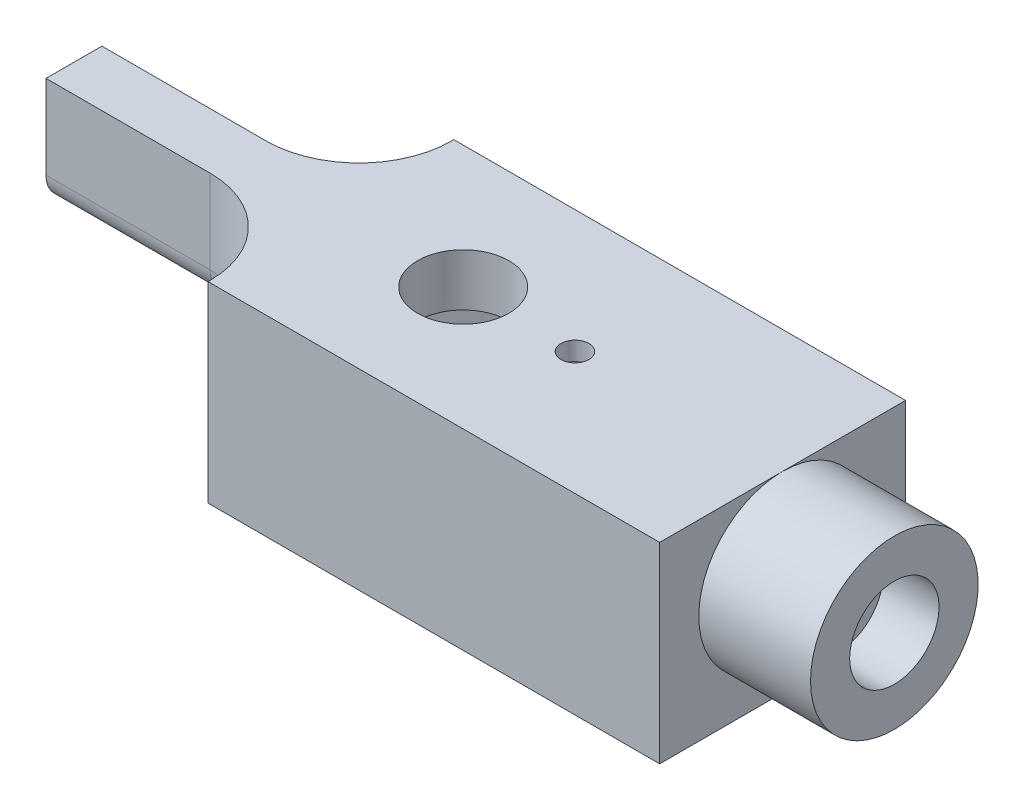
SolidWorks part; units mm, degrees
ref_plane "Plan de face" through (0, 0, 0) normal (0, 0, 1) x (1, 0, 0)
ref_plane "Plan de dessus" through (0, 0, 0) normal (0, 1, 0) x (1, 0, 0)
ref_plane "Plan de droite" through (0, 0, 0) normal (1, 0, 0) x (0, 0, -1)
sketch "Esquisse1" plane through (0, 0, 0) normal (0, 1, 0) x (1, 0, 0)
  line L0 (0, 5.5) -> (22.05, 5.5) construction
  line L1 (0, 0) -> (22.05, 0) construction
  line L2 (0, 0) -> (0, 11) construction
  line L3 (0, 11) -> (22.05, 11) construction
  line L4 (22.05, 0) -> (22.05, 11) construction
  line L5 (22.05, 11) -> (13.95, 0) construction
  line L6 (13.95, 0) -> (13.95, 11) construction
  line L7 (16.45, 11) -> (13.95, 8.5) construction
  line L8 (16.45, 0) -> (16.45, 11) construction
  line L10 (13.95, 2.5) -> (16.45, 0) construction
  circle A0 centre (6, 5.5) radius 5 construction
  circle A1 centre (12, 5.5) radius 5 construction
  circle A2 centre (18, 5.5) radius 1.25 construction
  point P14 (1, 5.5)
  dimension "D1" = 10
  dimension "D3" = 2.5
  dimension "D2" = 6
  dimension "D4" = 6
  dimension "D5" = 1
  dimension "D6" = 11
  dimension "D7" = 8.1
  dimension "D8" = 2.5
sketch "Esquisse2" plane through (0, 0, 0) normal (0, 1, 0) x (1, 0, 0)
  line L0 (11.025, 11) -> (11.025, 12.1) construction
  line L1 (0, 11) -> (22.05, 11)
  line L2 (0, 11) -> (0, 0)
  line L3 (0, 0) -> (22.05, 0)
  line L4 (22.05, 11) -> (22.05, 0)
  line L5 (-1.1, 12.1) -> (23.15, 12.1)
  line L6 (-1.1, 12.1) -> (-1.1, -1.1)
  line L7 (-1.1, -1.1) -> (23.15, -1.1)
  line L8 (23.15, 12.1) -> (23.15, -1.1)
  line L9 (0, 2.5) -> (2.5, 0)
  line L10 (-1.1, 5.5) -> (0, 5.5) construction
  line L12 (22.05, 8.5) -> (19.55, 11)
  line L13 (19.55, 11) -> (19.55, 0) construction
  line L14 (19.55, 0) -> (22.05, 2.5)
  line L15 (0.5, 0.5) -> (21.55, 0.5) construction
  line L16 (2.5, 11) -> (0, 8.5)
  line L18 (0.5, 0.5) -> (0.5, 10.5) construction
  line L19 (0.5, 10.5) -> (21.55, 10.5) construction
  line L20 (21.55, 0.5) -> (21.55, 10.5) construction
  circle A0 centre (0.5, 0.5) radius 0.5
  circle A1 centre (21.55, 0.5) radius 0.5
  circle A2 centre (21.55, 10.5) radius 0.5
  circle A3 centre (0.5, 10.5) radius 0.5
  dimension "D3" = 1
  dimension "D1" = 1.1
  dimension "D2" = 2.5
extrude "Boss.-Extru.1" add sketch "Esquisse2" along normal blind 9.3 contours L8 L5 L6 L7 L1 L4 L3 L2 | L16 L1 L2 | L12 L4 L1 | L14 L3 L4 | A1 L3 L4 | A2 L4 L1 | A0 L2 L3 | A3 L1 L2 | A0 L3 L9 L2
sketch "Esquisse3" plane through (0, 9.3, 0) normal (0, 1, 0) x (1, 0, 0)
  line L0 (-1.1, 12.1) -> (-1.1, -1.1) construction
  line L1 (23.15, -1.1) -> (-1.1, -1.1)
  line L2 (23.15, -1.1) -> (23.15, 12.1)
  line L3 (23.15, 12.1) -> (-1.1, 12.1)
  line L4 (-1.1, -1.1) -> (-1.1, 12.1)
  line L5 (-1.1, 12.1) -> (23.15, 12.1) construction
  circle A0 centre (6, 5.5) radius 2.45
  circle A1 centre (12, 5.5) radius 0.75
  dimension "D1" = 4.9
  dimension "D2" = 1.5
extrude "Boss.-Extru.2" add sketch "Esquisse3" along normal blind 1
sketch "Esquisse4" plane through (23.15, 0, 0) normal (1, 0, 0) x (0, 0, -1)
  line L0 (-1.1, 9.3) -> (12.1, 9.3) construction
  line L1 (-1.1, 10.3) -> (-1.1, 0) construction
  line L2 (12.1, 10.3) -> (12.1, 0) construction
  line L3 (-1.1, 10.3) -> (12.1, 10.3) construction
  line L4 (5.5, 5.8) -> (5.5, 9.3) construction
  circle A0 centre (5.5, 5.8) radius 3.5 construction
  circle A1 centre (5.5, 5.8) radius 1
  dimension "D1" = 1
  dimension "D2" = 7
  dimension "D3" = 2
extrude "Enlèv. mat.-Extru.1" cut sketch "Esquisse4" against normal through all
ref_axis "Axe1" through (-19.0316, 5.8, -5.5) along (1, 0, 0)
ref_plane "Plan1" through (0, 0, -5.5) normal (0, 0, 1) x (1, 0, 0)
sketch "Esquisse5" plane through (0, 0, -5.5) normal (0, 0, 1) x (1, 0, 0)
  line L1 (26.15, 5.8) -> (26.15, 8.2)
  line L2 (26.15, 8.2) -> (29.15, 8.2)
  line L3 (29.15, 8.2) -> (29.15, 10.3)
  line L4 (29.15, 10.3) -> (22.05, 10.3)
  line L5 (22.05, 10.3) -> (22.05, 5.8)
  line L8 (-19.0316, 5.8) -> (28.6752, 5.8) construction
  line L9 (23.15, 10.3) -> (-1.1, 10.3) construction
  line L10 (26.15, 8.2) -> (22.05, 8.2) construction
  line L11 (22.05, 5.8) -> (26.15, 5.8)
  line L12 (0.9, 5.8) -> (0.9, 6.3)
  line L13 (0.9, 6.3) -> (-1.1, 6.3)
  line L14 (-1.1, 6.3) -> (-1.1, 7.3) construction
  line L15 (-1.1, 7.3) -> (1.9, 7.3)
  line L16 (1.9, 7.3) -> (1.9, 5.8)
  line L17 (1.9, 5.8) -> (0.9, 5.8)
  line L19 (23.15, 10.3) -> (23.15, 0) construction
  line L21 (22.05, 9.3) -> (22.05, 0) construction
  line L22 (-1.1, 5.8) -> (-1.1, 0) construction
  line L24 (-1.1, 7.3) -> (-14.9, 7.3)
  line L25 (-1.1, 7.3) -> (-1.1, 6.3)
  line L26 (-1.1, 6.3) -> (-14.9, 6.3)
  line L27 (-14.9, 7.3) -> (-14.9, 6.3)
  dimension "D1" = 3
  dimension "D2" = 2.4
  dimension "D3" = 1
  dimension "D4" = 0.5
  dimension "D5" = 1
  dimension "D6" = 3
  dimension "D7" = 13.8
  dimension "D8" = 3
revolve "Révolution1" add sketch "Esquisse5" angle 360 about axis through (-19.0316, 5.8, -5.5) along (1, 0, 0)
sketch "Esquisse6" plane through (-14.9, 0, 0) normal (-1, 0, 0) x (0, 0, 1)
  line L0 (-12.1, 10.3) -> (1.1, 10.3) construction
  line L1 (-7, 5.8) -> (-4, 5.8) construction
  line L2 (-7, 5.8) -> (-7, 10.3)
  line L3 (-7, 10.3) -> (-4, 10.3)
  line L4 (-4, 5.8) -> (-4, 10.3)
  arc A0 (-7, 5.8) -> (-4, 5.8) centre (-5.5, 5.8) cw
  circle A1 centre (-5.5, 5.8) radius 1.5 construction
  point P14 (-5.5, 5.8)
extrude "Boss.-Extru.3" add sketch "Esquisse6" against normal up to surface (13.8 mm away) up to face at (-1.1, 5.8, -7)
fillet "Congé1" radius 5 3 edges at (-1.1, 8.05, -7) (-1.1, 4.3, -5.5) (-1.1, 8.05, -4)
sketch "Esquisse8" plane through (0, 9.3, 0) normal (0, -1, 0) x (1, 0, 0)
  circle A0 centre (6, -5.5) radius 3.45
  circle A1 centre (6, -5.5) radius 2.45
  circle A2 centre (6, -5.5) radius 2.45 construction
  dimension "D1" = 1
extrude "Boss.-Extru.4" add sketch "Esquisse8" along normal blind 1.8
sketch "Esquisse9" plane through (-14.9, 0, 0) normal (-1, 0, 0) x (0, 0, 1)
  circle A0 centre (-5.5, 5.8) radius 0.7
  circle A1 centre (-5.5, 5.8) radius 0.5 construction
  dimension "D1" = 1.4
extrude "Enlèv. mat.-Extru.2" cut sketch "Esquisse9" against normal blind 8
